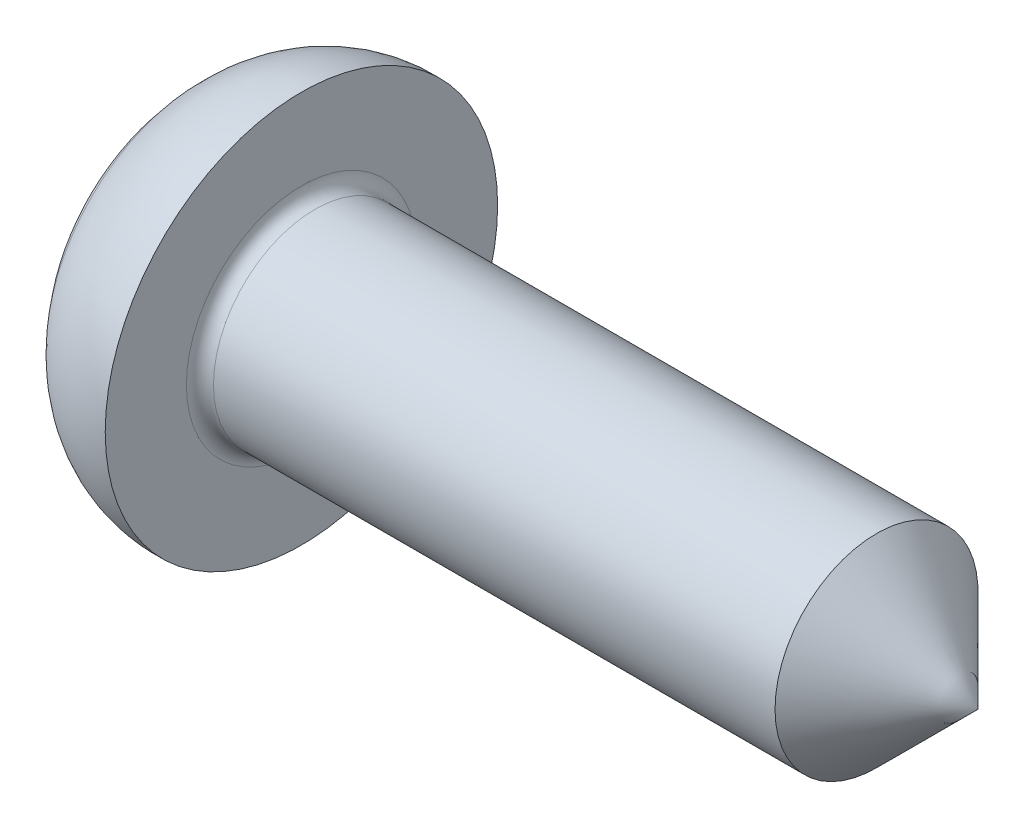
SolidWorks part; units mm, degrees
ref_plane "Front" through (0, 0, 0) normal (0, 0, 1) x (1, 0, 0)
ref_plane "Top" through (0, 0, 0) normal (0, 1, 0) x (1, 0, 0)
ref_plane "Right" through (0, 0, 0) normal (1, 0, 0) x (0, 0, -1)
sketch "Sketch1" plane through (0, 0, 0) normal (0, 1, 0) x (1, 0, 0)
  line L0 (-13.6293, 0) -> (11.3577, 0) construction
  line L1 (2.37, 1.5) -> (12.37, 1.5)
  line L2 (12.37, 1.5) -> (12.37, 0)
  line L3 (2.37, 1.5) -> (2.37, 2.9)
  line L4 (12.37, 0) -> (0, 0)
  arc A0 (2.37, 2.9) -> (0.8698, 2.2711) centre (2.2837, 1.002) ccw
  arc A1 (0, 0) -> (0.8698, 2.2711) centre (3.4, 0) cw
  dimension "r2" = 1.9
  dimension "r1" = 3.4
  dimension "d" = 3
  dimension "dk" = 5.8
  dimension "l" = 10
  dimension "k" = 2.37
revolve "Revolve1" add sketch "Sketch1" angle 360 about L0
cosmetic thread "ThreadCosmetic1" [suppressed] parameters "l0"=4.5, "dm"=2.75
fillet "Fillet2" radius 0.2 1 edges at (2.37, 0, 1.5)
sketch "Sketch4" plane through (0, 0, 0) normal (0, 1, 0) x (1, 0, 0)
  line L0 (4.7828, 0) -> (7.1391, 0) construction
  line L2 (13.1035, 0) -> (13.1035, 21)
  line L3 (13.1035, 21) -> (-8.63, 21)
  line L4 (-8.63, 21) -> (12.37, 0)
  line L5 (12.37, 0) -> (13.1035, 0)
  line L7 (12.37, -1.5) -> (12.37, 1.5) construction
  dimension "D1" = 45
  dimension "D2" = 0.7335
  dimension "D3" = 21
revolve "Cut-Revolve1" cut sketch "Sketch4" angle 360 about L0
sketch "Sketch2" plane through (0, 0, 0) normal (1, 0, 0) x (0, 0, -1)
  line L0 (-2.278, 0) -> (2.6944, 0) construction
  line L1 (0, -2.1234) -> (0, 2.1948) construction
  line L2 (-0.4625, 0.4625) -> (-1.85, 0.4625)
  line L3 (0.4625, -1.85) -> (-0.4625, -1.85)
  line L4 (0.4625, -1.85) -> (0.4625, -0.4625)
  line L5 (0.4625, 1.85) -> (-0.4625, 1.85)
  line L6 (-0.4625, -1.85) -> (-0.4625, -0.4625)
  line L7 (1.85, 0.4625) -> (0.4625, 0.4625)
  line L8 (1.85, 0.4625) -> (1.85, -0.4625)
  line L9 (1.85, -0.4625) -> (0.4625, -0.4625)
  line L10 (-1.85, 0.4625) -> (-1.85, -0.4625)
  line L11 (-0.4625, 0.4625) -> (-0.4625, 1.85)
  line L12 (-0.4625, -0.4625) -> (-1.85, -0.4625)
  line L13 (0.4625, 0.4625) -> (0.4625, 1.85)
  point P19 (-0.4625, 0.4625)
  point P22 (0.4625, 0.4625)
  point P27 (-0.4625, -0.4625)
  dimension "m" = 3.7
  dimension "D2" = 3.7
  dimension "D3" = 0.925
  dimension "D4" = 0.925
ref_plane "Plane1" through (2.62, 0, 0) normal (1, 0, 0) x (0, 0, -1)
sketch "Sketch5" plane through (2.62, 0, 0) normal (1, 0, 0) x (0, 0, -1)
  point P0 (0, 0)
loft "Cut-Loft1" cut profiles "Sketch5", "Sketch2"
sketch "Sketch6" plane through (0, 0, 0) normal (0, 0, 1) x (1, 0, 0)
  line L0 (6.37, 1.7) -> (6.495, 1.7)
  line L1 (6.495, 1.7) -> (6.495, 1.5)
  line L2 (6.495, 1.5) -> (6.4325, 1.3917)
  line L3 (6.37, 1.5) -> (6.4325, 1.3917)
  line L4 (6.37, 1.7) -> (6.37, 1.5)
  line L5 (10.7743, 0) -> (0, 0) construction
  line L6 (6.37, 1.5) -> (6.495, 1.5) construction
  line L7 (6.4325, 1.5) -> (6.4325, 1.3917) construction
  line L8 (10.87, 1.5) -> (2.57, 1.5) construction
  point P5 (6.4325, 1.7)
  dimension "D1" = 0.2
  dimension "D2" = 0.125
  dimension "D3" = 6
revolve "Cut-Revolve10" [suppressed] cut sketch "Sketch6" angle 360 about L5
pattern_linear "LPattern10" [suppressed] count 24 spacing 0.25 along (1, 0, 0)
equation "\"D4@Sketch2\" = \"D3@Sketch2\""
equation "\"D2@Sketch2\" = \"m@Sketch2\""
equation "\"D3@Sketch2\" = \"m@Sketch2\" / 4"
equation "\"D2@Sketch6\" = (  \"d@Sketch1\" - \"dm@ThreadCosmetic1\" )  / 2"
equation "\"D3@Sketch6\" = \"l0@ThreadCosmetic1\" + \"d@Sketch1\" / 2"
equation "\"D3@LPattern10\" = \"D2@Sketch6\" *2"
equation "\"D1@LPattern10\" = \"D3@Sketch6\" / \"D3@LPattern10\""
